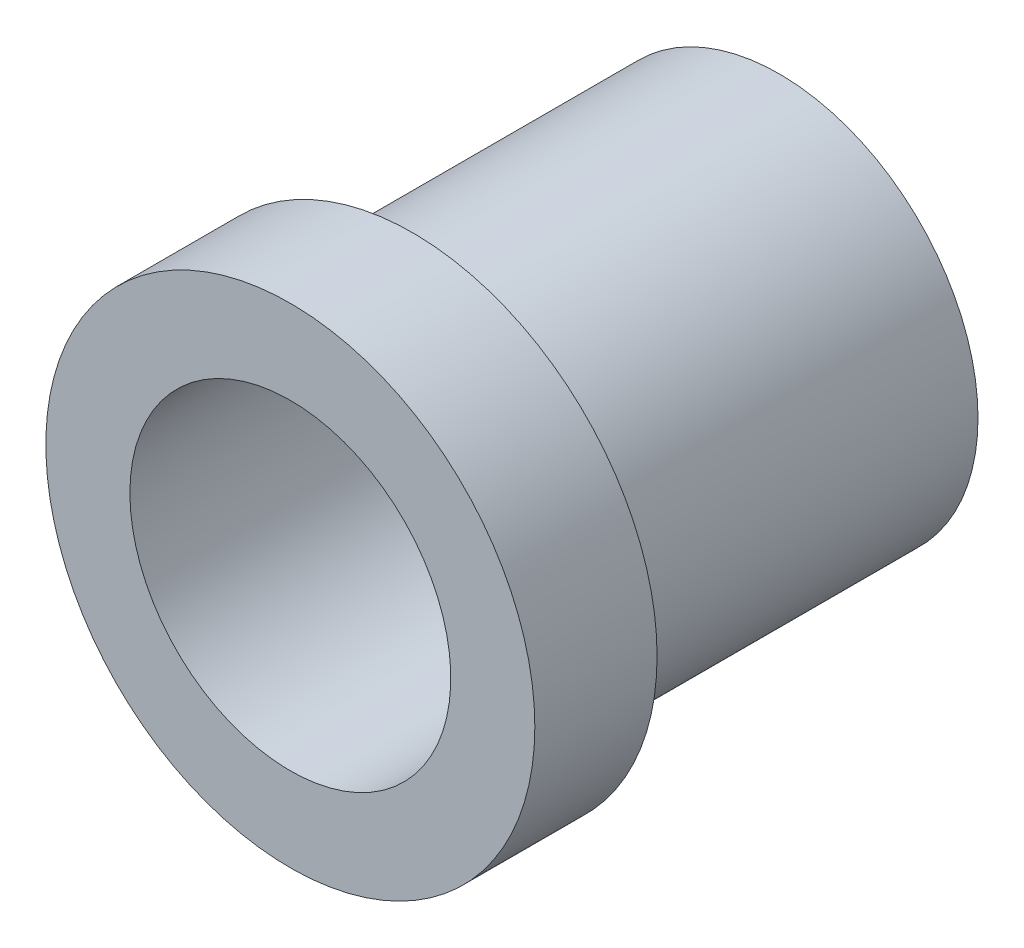
SolidWorks part; units mm, degrees
ref_plane "Front Plane" through (0, 0, 0) normal (0, 0, 1) x (1, 0, 0)
ref_plane "Top Plane" through (0, 0, 0) normal (0, 1, 0) x (1, 0, 0)
ref_plane "Right Plane" through (0, 0, 0) normal (1, 0, 0) x (0, 0, -1)
sketch "Sketch1" plane through (0, 0, 0) normal (0, 0, 1) x (1, 0, 0)
  circle A0 centre (0, 0) radius 6.5
  dimension "D1" = 13
extrude "Boss-Extrude1" add sketch "Sketch1" along normal blind 12 contours A0
sketch "Sketch2" plane through (0, 0, 0) normal (0, 0, 1) x (1, 0, 0)
  circle A0 centre (0, 0) radius 5.25
  dimension "D1" = 10.5
extrude "Cut-Extrude1" cut sketch "Sketch2" along normal blind 14
sketch "Sketch4" plane through (0, 0, 12) normal (0, 0, 1) x (1, 0, 0)
  circle A0 centre (0, 0) radius 8
  dimension "16" = 16
extrude "Boss-Extrude2" add sketch "Sketch4" along normal blind 4
sketch "Sketch5" plane through (0, 0, 12) normal (0, 0, -1) x (-1, 0, 0)
  circle A0 centre (0, 0) radius 5.25
extrude "Cut-Extrude2" cut sketch "Sketch5" against normal through all
